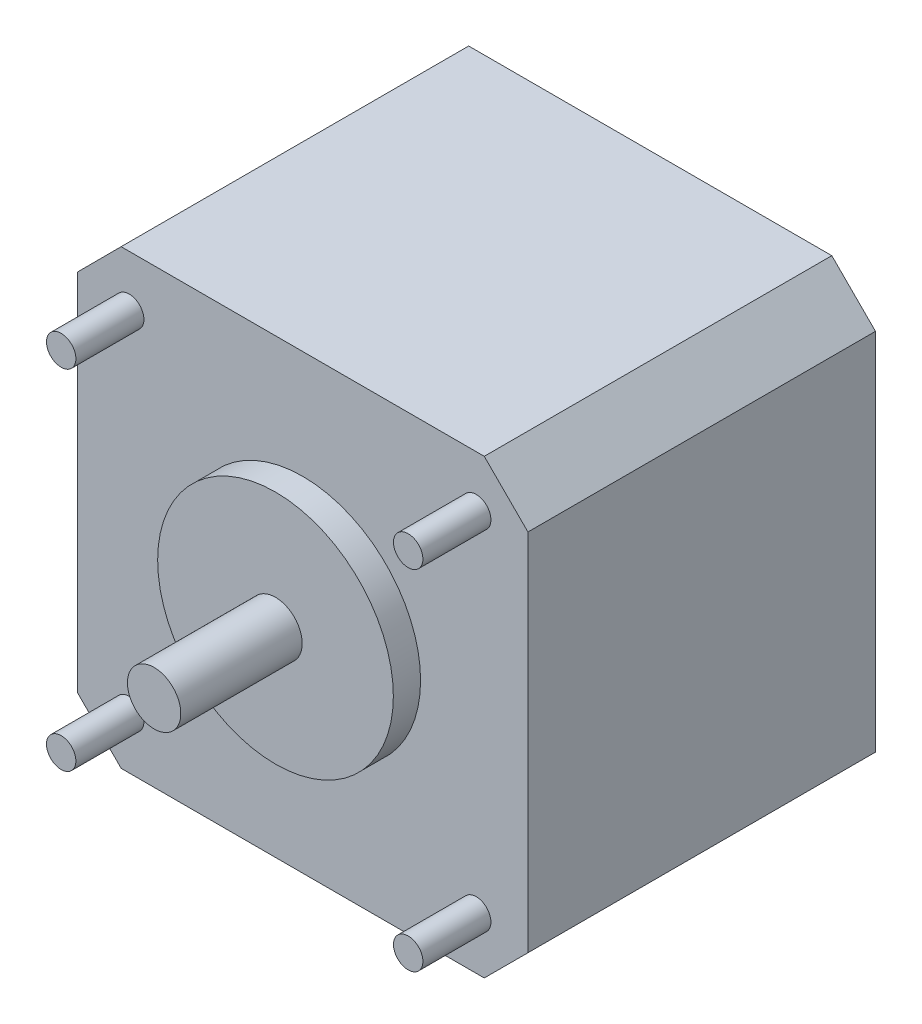
SolidWorks part; units mm, degrees
ref_plane "Front Plane" through (0, 0, 0) normal (0, 0, 1) x (1, 0, 0)
ref_plane "Top Plane" through (0, 0, 0) normal (0, 1, 0) x (1, 0, 0)
ref_plane "Right Plane" through (0, 0, 0) normal (1, 0, 0) x (0, 0, -1)
sketch "Sketch1" plane through (0, 0, 0) normal (0, 0, 1) x (1, 0, 0)
  line L0 (0, 42.164) -> (42.037, 0) construction
  line L1 (0, 0) -> (42.037, 0)
  line L2 (0, 0) -> (0, 42.164)
  line L3 (0, 42.164) -> (42.037, 42.164)
  line L4 (42.037, 0) -> (42.037, 42.164)
  line L5 (0, 0) -> (42.037, 42.164) construction
  line L6 (0, 38.0808) -> (4.0709, 42.164)
  line L7 (4.077, 0) -> (0, 4.077)
  line L8 (37.96, 0) -> (42.037, 4.077)
  line L9 (37.96, 42.164) -> (42.037, 38.087)
  dimension "D1" = 42.037
  dimension "D2" = 42.164
  dimension "D3" = 5.7658
  dimension "D4" = 5.7658
  dimension "D5" = 5.7658
  dimension "D6" = 5.7658
extrude "Boss-Extrude4" add sketch "Sketch1" along normal blind 32.4358 contours L9 L3 L6 L2 L7 L1 L8 L4
sketch "Sketch4" plane through (0, 0, 32.4358) normal (0, 0, 1) x (1, 0, 0)
  circle A0 centre (21.0185, 21.0789) radius 10.9982
  dimension "D1" = 21.9964
extrude "Boss-Extrude5" add sketch "Sketch4" along normal blind 2.54
sketch "Sketch5" plane through (0, 0, 34.9758) normal (0, 0, 1) x (1, 0, 0)
  circle A0 centre (21.0185, 21.0789) radius 2.4892
  dimension "D1" = 4.9784
extrude "Boss-Extrude6" add sketch "Sketch5" along normal blind 11.3284
sketch "Sketch6" plane through (0, 0, 32.4358) normal (0, 0, 1) x (1, 0, 0)
  line L0 (0, 37.338) -> (4.826, 37.338) construction
  line L1 (0, 4.077) -> (0, 38.0808) construction
  line L2 (4.826, 37.338) -> (4.826, 42.164) construction
  line L3 (4.0709, 42.164) -> (37.96, 42.164) construction
  line L4 (0, 4.826) -> (4.826, 4.826) construction
  line L5 (4.826, 4.826) -> (4.826, 0) construction
  line L6 (4.077, 0) -> (37.96, 0) construction
  line L7 (37.211, 0) -> (37.211, 4.826) construction
  line L8 (37.211, 4.826) -> (42.037, 4.826) construction
  line L9 (42.037, 4.077) -> (42.037, 38.087) construction
  line L10 (42.037, 37.338) -> (37.211, 37.338) construction
  line L11 (37.211, 37.338) -> (37.211, 42.164) construction
  circle A0 centre (4.826, 37.338) radius 1.3716
  circle A1 centre (4.826, 4.826) radius 1.3716
  circle A2 centre (37.211, 4.826) radius 1.3716
  circle A3 centre (37.211, 37.338) radius 1.3716
  dimension "D3" = 2.7432
  dimension "D6" = 2.7432
  dimension "D11" = 2.7432
  dimension "D12" = 2.7432
  dimension "D1" = 4.826
  dimension "D2" = 4.826
  dimension "D4" = 4.826
  dimension "D5" = 4.826
  dimension "D7" = 4.826
  dimension "D8" = 4.826
  dimension "D9" = 4.826
  dimension "D10" = 4.826
extrude "Boss-Extrude7" add sketch "Sketch6" along normal blind 6.35
sketch "Sketch7" plane through (0, 0, 0) normal (0, 0, -1) x (-1, 0, 0)
  circle A0 centre (-21.0185, 21.0789) radius 2.4892
  dimension "D1" = 4.9784
extrude "Boss-Extrude8" add sketch "Sketch7" along normal blind 0.9144
